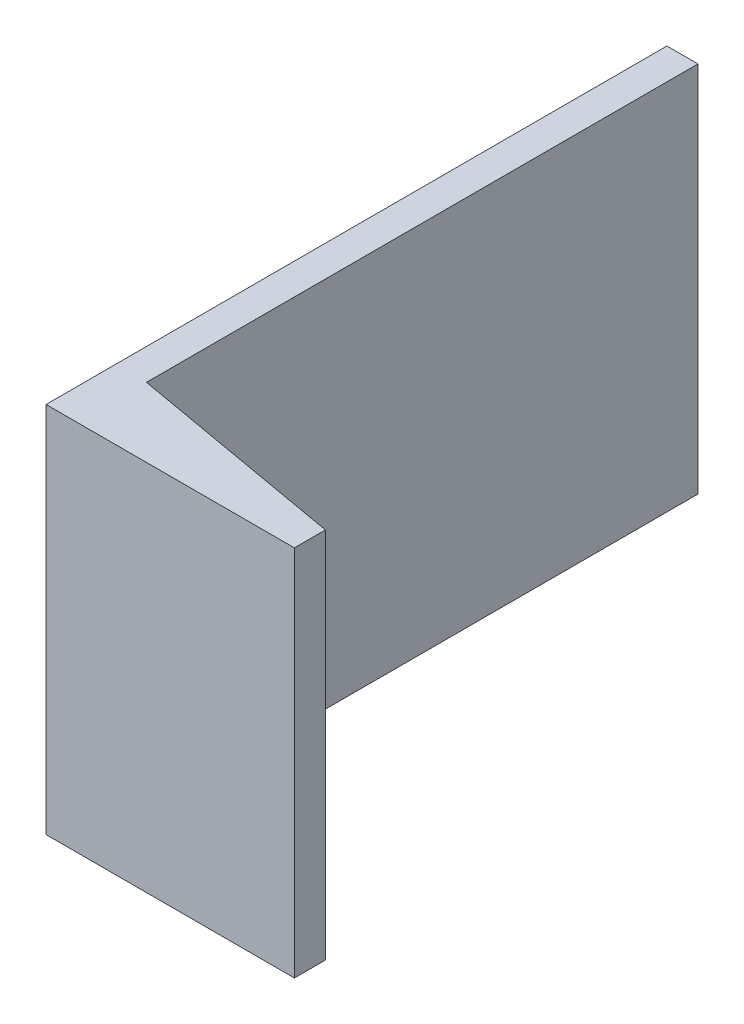
SolidWorks part; units mm, degrees
ref_plane "Front Plane" through (0, 0, 0) normal (0, 0, 1) x (1, 0, 0)
ref_plane "Top Plane" through (0, 0, 0) normal (0, 1, 0) x (1, 0, 0)
ref_plane "Right Plane" through (0, 0, 0) normal (1, 0, 0) x (0, 0, -1)
sketch "Sketch1" plane through (0, 0, 0) normal (0, 1, 0) x (1, 0, 0)
  line L0 (0, 0) -> (50.8, 0)
  line L1 (50.8, 0) -> (50.8, 6.35)
  line L2 (50.8, 6.35) -> (6.35, 14.1877)
  line L3 (6.35, 14.1877) -> (6.35, 127)
  line L4 (6.35, 127) -> (0, 127)
  line L5 (0, 127) -> (0, 0)
  dimension "D1" = 6.35
  dimension "D2" = 127
  dimension "D3" = 50.8
  dimension "D4" = 6.35
  dimension "D5" = 10
extrude "Extrude1" add sketch "Sketch1" along normal blind 76.2
